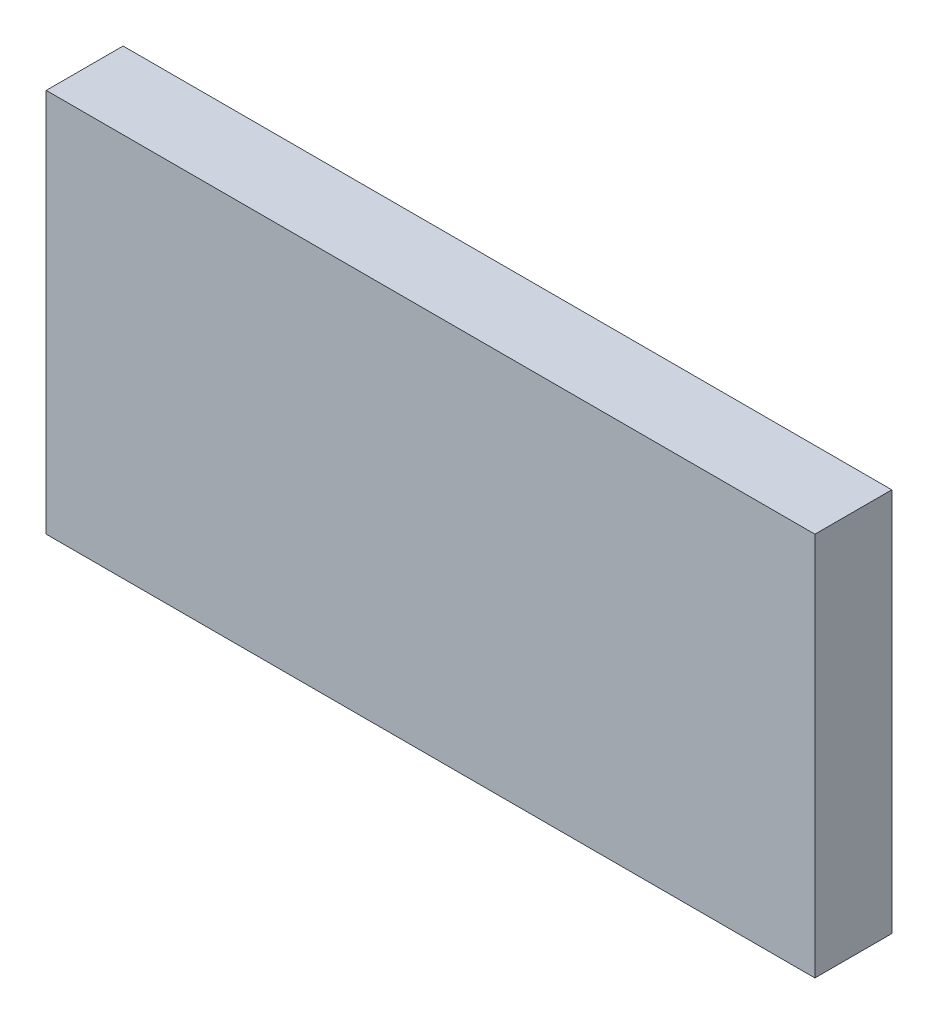
SolidWorks part; units mm, degrees
ref_plane "Front Plane" through (0, 0, 0) normal (0, 0, 1) x (1, 0, 0)
ref_plane "Top Plane" through (0, 0, 0) normal (0, 1, 0) x (1, 0, 0)
ref_plane "Right Plane" through (0, 0, 0) normal (1, 0, 0) x (0, 0, -1)
sketch "Sketch1" plane through (0, 0, 0) normal (0, 0, 1) x (1, 0, 0)
  line L1 (-20, 10) -> (20, 10)
  line L2 (-20, 10) -> (-20, -10)
  line L3 (-20, -10) -> (20, -10)
  line L4 (20, 10) -> (20, -10)
  line L5 (-20, 10) -> (20, -10) construction
  line L6 (-20, -10) -> (20, 10) construction
  point P0 (0, 0)
  dimension "D1" = 40
  dimension "D2" = 20
extrude "Boss-Extrude1" add sketch "Sketch1" along normal blind 4
